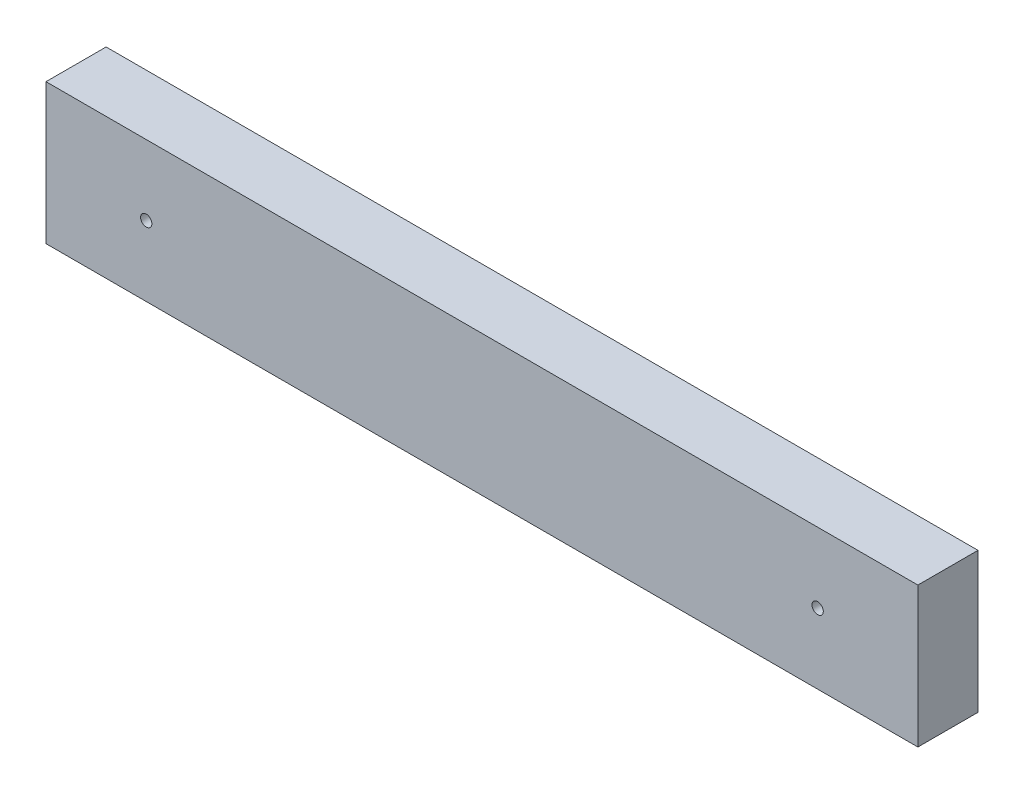
SolidWorks part; units mm, degrees
material "Pine"
ref_plane "Front Plane" through (0, 0, 0) normal (0, 0, 1) x (1, 0, 0)
ref_plane "Top Plane" through (0, 0, 0) normal (0, 1, 0) x (1, 0, 0)
ref_plane "Right Plane" through (0, 0, 0) normal (1, 0, 0) x (0, 0, -1)
sketch "Sketch1" plane through (0, 0, 0) normal (1, 0, 0) x (0, 0, -1)
  line L0 (0, 0) -> (38.1, 0)
  line L1 (0, 0) -> (0, 88.9)
  line L2 (38.1, 0) -> (38.1, 88.9)
  line L3 (0, 88.9) -> (38.1, 88.9)
  dimension "D1" = 38.1
  dimension "D2" = 88.9
extrude "Boss-Extrude1" add sketch "Sketch1" along normal blind 552.45
sketch "Sketch2" plane through (0, 0, 0) normal (0, 0, 1) x (1, 0, 0)
  line L0 (0, 88.9) -> (0, 0) construction
  line L1 (552.45, 88.9) -> (552.45, 0) construction
  line L2 (552.45, 88.9) -> (0, 88.9) construction
  circle A0 centre (63.5, 44.45) radius 3.5719
  circle A1 centre (488.95, 44.45) radius 3.5719
  dimension "D5" = 7.1437
  dimension "D6" = 7.1437
  dimension "D1" = 63.5
  dimension "D2" = 63.5
  dimension "D3" = 44.45
  dimension "D4" = 44.45
extrude "Cut-Extrude1" cut sketch "Sketch2" against normal through all
